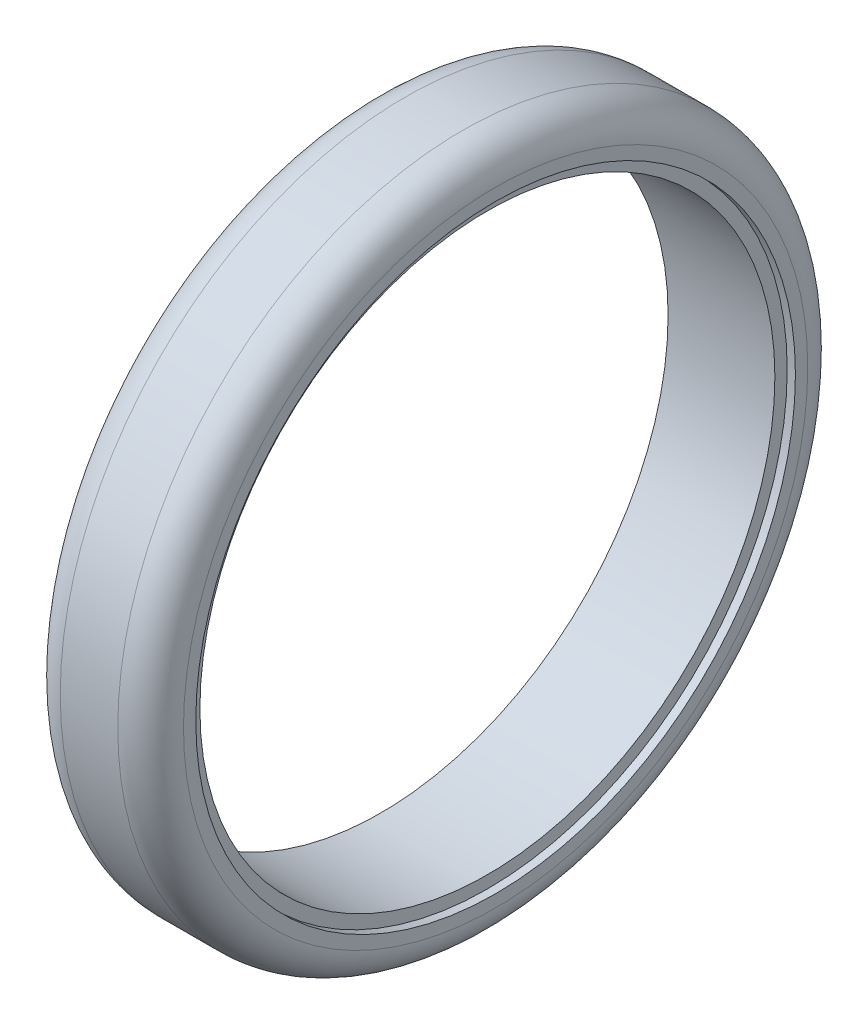
SolidWorks part; units mm, degrees
material "Rubber"
ref_plane "Front Plane" through (0, 0, 0) normal (0, 0, 1) x (1, 0, 0)
ref_plane "Top Plane" through (0, 0, 0) normal (0, 1, 0) x (1, 0, 0)
ref_plane "Right Plane" through (0, 0, 0) normal (1, 0, 0) x (0, 0, -1)
sketch "Sketch1" plane through (0, 0, 0) normal (0, 0, 1) x (1, 0, 0)
  line L0 (0, 0) -> (0, 35)
  line L1 (-6.5, 35) -> (6.5, 35)
  line L2 (-6.5, 35) -> (-6.5, 36.5)
  line L3 (-6.5, 36.5) -> (-7.5, 36.5)
  line L4 (-7.5, 36.5) -> (-7.5, 38)
  line L5 (6.5, 35) -> (6.5, 36.5)
  line L6 (6.5, 36.5) -> (7.5, 36.5)
  line L7 (7.5, 36.5) -> (7.5, 38)
  line L8 (-3.5, 42) -> (3.5, 42)
  line L9 (-2.5422, 42) -> (2.4578, 42)
  line L10 (-3.2922, 42) -> (-1.7922, 42)
  line L11 (-3.2922, 43) -> (-1.7922, 43)
  line L12 (-3.2922, 43) -> (-3.2922, 41)
  line L13 (-3.2922, 41) -> (-1.7922, 41)
  line L14 (-1.7922, 43) -> (-1.7922, 41)
  line L15 (-3.2922, 43) -> (-1.7922, 41) construction
  line L16 (-3.2922, 41) -> (-1.7922, 43) construction
  line L17 (1.7078, 43) -> (3.2078, 43)
  line L18 (1.7078, 43) -> (1.7078, 41)
  line L19 (1.7078, 41) -> (3.2078, 41)
  line L20 (3.2078, 43) -> (3.2078, 41)
  line L21 (1.7078, 43) -> (3.2078, 41) construction
  line L22 (1.7078, 41) -> (3.2078, 43) construction
  line L23 (3.2078, 42) -> (1.7078, 42)
  arc A0 (7.5, 38) -> (3.5, 42) centre (3.5, 38) ccw
  arc A1 (-3.5, 42) -> (-7.5, 38) centre (-3.5, 38) ccw
  point P6 (0, 35)
  point P14 (7.5, 42)
  point P17 (-7.5, 42)
  point P21 (-0.0422, 42)
  dimension "D6" = 4
  dimension "D1" = 35
  dimension "D2" = 13
  dimension "D3" = 1.5
  dimension "D4" = 5.5
  dimension "D5" = 1
  dimension "D7" = 5
  dimension "D8" = 1.5
  dimension "D9" = 1.5
  dimension "D10" = 2
  dimension "2" = 2
sketch "Sketch2" plane through (0, 0, 0) normal (0, 1, 0) x (1, 0, 0)
  line L0 (-13.4108, 0) -> (13.3247, 0) construction
revolve "Revolve1" add sketch "Sketch1" angle 360 about L0
fillet "Fillet7" [suppressed] radius 1
fillet "Fillet8" [suppressed] radius 1
fillet "Fillet9" [suppressed] radius 1
ref_plane "Plane1" through (7.5, 0, 0) normal (1, 0, 0) x (0, 0, -1)
sketch "Sketch5" plane through (7.5, 0, 0) normal (1, 0, 0) x (0, 0, -1)
  line L0 (0, 0) -> (0, 41.5)
  line L1 (0, 41) -> (0, 42.002)
  line L2 (5, 40.694) -> (5, 41.7033)
  line L3 (16.2623, 37.6369) -> (16.5466, 38.6053)
  line L4 (11.551, 39.3392) -> (11.8333, 40.3006)
  line L5 (26.2071, 31.5308) -> (26.7528, 32.3798)
  line L6 (22.1663, 34.4914) -> (22.708, 35.3343)
  line L7 (34.0288, 22.8701) -> (34.7915, 23.5311)
  line L8 (30.9857, 26.8493) -> (31.743, 27.5054)
  line L9 (39.0936, 12.3567) -> (40.0117, 12.776)
  line L10 (37.2949, 17.032) -> (38.2063, 17.4482)
  line L11 (40.9913, 0.8422) -> (41.9904, 0.9859)
  line L12 (40.5827, 5.8349) -> (41.5744, 5.9775)
  line L13 (39.5682, -10.7405) -> (40.5672, -10.8841)
  line L14 (40.5827, -5.8349) -> (41.5744, -5.9775)
  line L15 (34.9395, -21.4531) -> (35.8576, -21.8723)
  line L16 (37.2949, -17.032) -> (38.2063, -17.4482)
  line L17 (27.4802, -30.4276) -> (28.2429, -31.0886)
  line L18 (30.9857, -26.8493) -> (31.743, -27.5054)
  line L19 (17.7946, -36.9372) -> (18.3402, -37.7862)
  line L20 (22.1663, -34.4914) -> (22.708, -35.3343)
  line L21 (6.6674, -40.4543) -> (6.9517, -41.4227)
  line L22 (11.551, -39.3392) -> (11.8333, -40.3006)
  line L23 (-5, -40.694) -> (-5, -41.7033)
  line L24 (0, -41) -> (0, -42.002)
  line L25 (-16.2623, -37.6369) -> (-16.5466, -38.6053)
  line L26 (-11.551, -39.3392) -> (-11.8333, -40.3006)
  line L27 (-26.2071, -31.5308) -> (-26.7528, -32.3798)
  line L28 (-22.1663, -34.4914) -> (-22.708, -35.3343)
  line L29 (-34.0288, -22.8701) -> (-34.7915, -23.5311)
  line L30 (-30.9857, -26.8493) -> (-31.743, -27.5054)
  line L31 (-39.0936, -12.3567) -> (-40.0117, -12.776)
  line L32 (-37.2949, -17.032) -> (-38.2063, -17.4482)
  line L33 (-40.9913, -0.8422) -> (-41.9904, -0.9859)
  line L34 (-40.5827, -5.8349) -> (-41.5744, -5.9775)
  line L35 (-39.5682, 10.7405) -> (-40.5672, 10.8841)
  line L36 (-40.5827, 5.8349) -> (-41.5744, 5.9775)
  line L37 (-34.9395, 21.4531) -> (-35.8576, 21.8723)
  line L38 (-37.2949, 17.032) -> (-38.2063, 17.4482)
  line L39 (-27.4802, 30.4276) -> (-28.2429, 31.0886)
  line L40 (-30.9857, 26.8493) -> (-31.743, 27.5054)
  line L41 (-17.7946, 36.9372) -> (-18.3402, 37.7862)
  line L42 (-22.1663, 34.4914) -> (-22.708, 35.3343)
  line L43 (-6.6674, 40.4543) -> (-6.9517, 41.4227)
  line L44 (-11.551, 39.3392) -> (-11.8333, 40.3006)
  arc A0 (0, 41) -> (5, 40.694) centre (0, 0) cw
  arc A1 (0, 42.002) -> (5, 41.7033) centre (0, 0) cw
  arc A2 (11.8333, 40.3006) -> (16.5466, 38.6053) centre (0, 0) cw
  arc A3 (11.551, 39.3392) -> (16.2623, 37.6369) centre (0, 0) cw
  arc A4 (22.708, 35.3343) -> (26.7528, 32.3798) centre (0, 0) cw
  arc A5 (22.1663, 34.4914) -> (26.2071, 31.5308) centre (0, 0) cw
  arc A6 (31.743, 27.5054) -> (34.7915, 23.5311) centre (0, 0) cw
  arc A7 (30.9857, 26.8493) -> (34.0288, 22.8701) centre (0, 0) cw
  arc A8 (38.2063, 17.4482) -> (40.0117, 12.776) centre (0, 0) cw
  arc A9 (37.2949, 17.032) -> (39.0936, 12.3567) centre (0, 0) cw
  arc A10 (41.5744, 5.9775) -> (41.9904, 0.9859) centre (0, 0) cw
  arc A11 (40.5827, 5.8349) -> (40.9913, 0.8422) centre (0, 0) cw
  arc A12 (41.5744, -5.9775) -> (40.5672, -10.8841) centre (0, 0) cw
  arc A13 (40.5827, -5.8349) -> (39.5682, -10.7405) centre (0, 0) cw
  arc A14 (38.2063, -17.4482) -> (35.8576, -21.8723) centre (0, 0) cw
  arc A15 (37.2949, -17.032) -> (34.9395, -21.4531) centre (0, 0) cw
  arc A16 (31.743, -27.5054) -> (28.2429, -31.0886) centre (0, 0) cw
  arc A17 (30.9857, -26.8493) -> (27.4802, -30.4276) centre (0, 0) cw
  arc A18 (22.708, -35.3343) -> (18.3402, -37.7862) centre (0, 0) cw
  arc A19 (22.1663, -34.4914) -> (17.7946, -36.9372) centre (0, 0) cw
  arc A20 (11.8333, -40.3006) -> (6.9517, -41.4227) centre (0, 0) cw
  arc A21 (11.551, -39.3392) -> (6.6674, -40.4543) centre (0, 0) cw
  arc A22 (0, -42.002) -> (-5, -41.7033) centre (0, 0) cw
  arc A23 (0, -41) -> (-5, -40.694) centre (0, 0) cw
  arc A24 (-11.8333, -40.3006) -> (-16.5466, -38.6053) centre (0, 0) cw
  arc A25 (-11.551, -39.3392) -> (-16.2623, -37.6369) centre (0, 0) cw
  arc A26 (-22.708, -35.3343) -> (-26.7528, -32.3798) centre (0, 0) cw
  arc A27 (-22.1663, -34.4914) -> (-26.2071, -31.5308) centre (0, 0) cw
  arc A28 (-31.743, -27.5054) -> (-34.7915, -23.5311) centre (0, 0) cw
  arc A29 (-30.9857, -26.8493) -> (-34.0288, -22.8701) centre (0, 0) cw
  arc A30 (-38.2063, -17.4482) -> (-40.0117, -12.776) centre (0, 0) cw
  arc A31 (-37.2949, -17.032) -> (-39.0936, -12.3567) centre (0, 0) cw
  arc A32 (-41.5744, -5.9775) -> (-41.9904, -0.9859) centre (0, 0) cw
  arc A33 (-40.5827, -5.8349) -> (-40.9913, -0.8422) centre (0, 0) cw
  arc A34 (-41.5744, 5.9775) -> (-40.5672, 10.8841) centre (0, 0) cw
  arc A35 (-40.5827, 5.8349) -> (-39.5682, 10.7405) centre (0, 0) cw
  arc A36 (-38.2063, 17.4482) -> (-35.8576, 21.8723) centre (0, 0) cw
  arc A37 (-37.2949, 17.032) -> (-34.9395, 21.4531) centre (0, 0) cw
  arc A38 (-31.743, 27.5054) -> (-28.2429, 31.0886) centre (0, 0) cw
  arc A39 (-30.9857, 26.8493) -> (-27.4802, 30.4276) centre (0, 0) cw
  arc A40 (-22.708, 35.3343) -> (-18.3402, 37.7862) centre (0, 0) cw
  arc A41 (-22.1663, 34.4914) -> (-17.7946, 36.9372) centre (0, 0) cw
  arc A42 (-11.8333, 40.3006) -> (-6.9517, 41.4227) centre (0, 0) cw
  arc A43 (-11.551, 39.3392) -> (-6.6674, 40.4543) centre (0, 0) cw
  dimension "D3" = 5
  dimension "D1" = 41.5
  dimension "D2" = 41
  dimension "D4" = 22
extrude "Cut-Extrude2" [suppressed] cut sketch "Sketch5" against normal through all contours A1 L1 L0 A0 L2 | L42 A40 L41 A41 | A43 L43 A42 L44 | A2 L3 A3 L4 | A4 L5 A5 L6 | A7 L7 A6 L8 | A8 L9 A9 L10 | A11 L11 A10 L12 | A12 L13 A13 L14 | A14 L15 A15 L16 | A16 L17 A17 L18 | A18 L19 A19 L20 | A21 L21 A20 L22 | A22 L23 A23 L24 | A24 L25 A25 L26 | A26 L27 A27 L28 | L30 A28 L29 A29 | A30 L31 A31 L32 | A33 L33 A32 L34 | A34 L35 A35 L36 | A36 L37 A37 L38 | A39 L39 A38 L40
